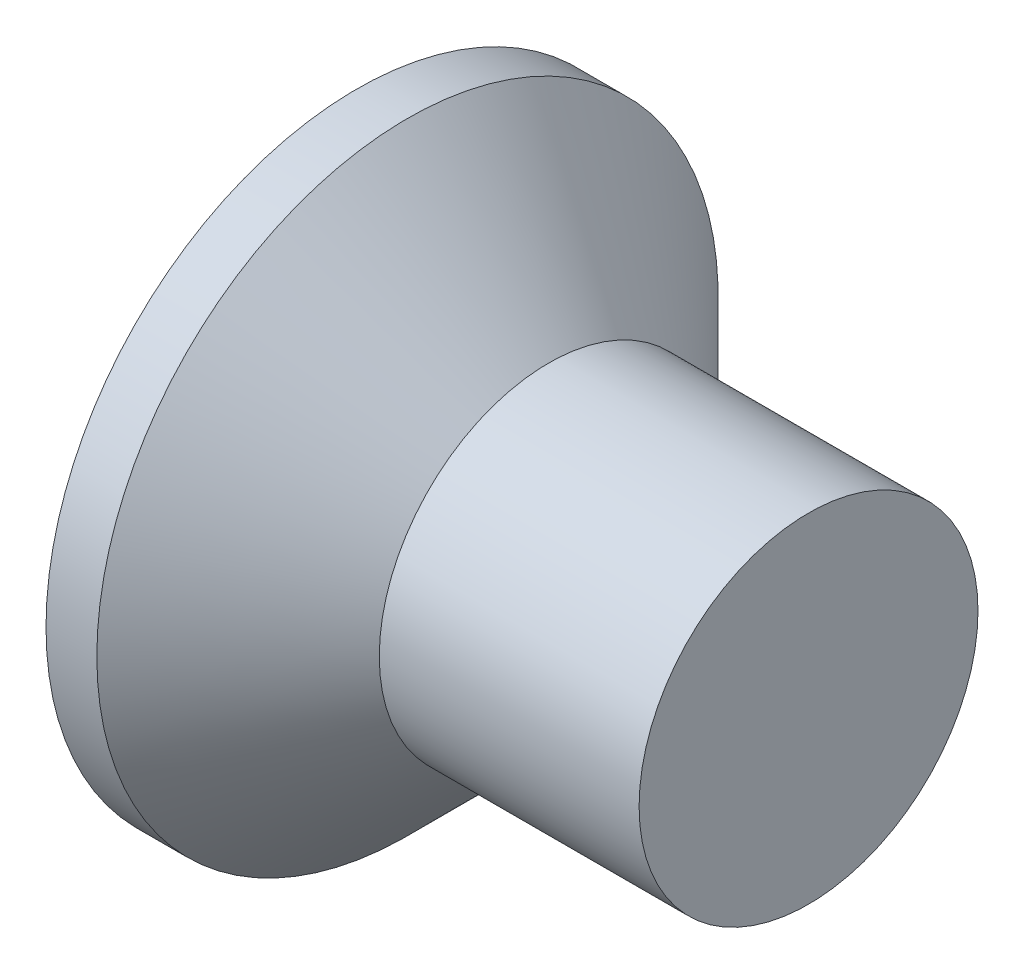
SolidWorks part; units mm, degrees
material "Plain Carbon Steel"
ref_plane "Plane1" through (0, 0, 0) normal (0, 0, 1) x (1, 0, 0)
ref_plane "Plane2" through (0, 0, 0) normal (0, 1, 0) x (1, 0, 0)
ref_plane "Plane3" through (0, 0, 0) normal (1, 0, 0) x (0, 0, -1)
sketch "BodySke" plane through (0, 0, 0) normal (0, 0, 1) x (1, 0, 0)
  line L0 (0, 0) -> (0, 2.75)
  line L1 (0, 2.75) -> (0.45, 2.75)
  line L2 (1.7, 1.5) -> (4, 1.5)
  line L3 (4, 1.5) -> (4, 0)
  line L4 (4, 0) -> (0, 0)
  line L5 (-6.35, 0) -> (82.55, 0) construction
  line L6 (1.7, -1.5) -> (4, -1.5) construction
  line L7 (0.45, -2.75) -> (1.7, -1.5) construction
  line L8 (0.45, 2.75) -> (1.7, 1.5)
  line L9 (0, -2.75) -> (0.45, -2.75) construction
  line L10 (2.2, 3.0875) -> (2.2, -6.4375) construction
  line L11 (0, 6.35) -> (0, -3.175) construction
  dimension "Diameter" = 3
  dimension "Length" = 4
  dimension "Head_ht" = 1.7
  dimension "Head_dia" = 5.5
  dimension "Head_ang" = 90
  dimension "D6" = 0.45
  dimension "Advance" = 0.5
  dimension "Thread_nom" = 4
revolve "Base-Revolve" add sketch "BodySke" angle 360 about L5
cosmetic thread "ThreadCosmetic" [suppressed] parameters "Thread_length"=1.8, "Thread_minor"=2.439
sketch "Sketch2" plane through (0, 0, 0) normal (-1, 0, 0) x (0, 0, 1)
  line L0 (-2.75, -0.5) -> (2.75, -0.5)
  line L1 (-2.75, -0.5) -> (-2.75, 0.5)
  line L2 (2.75, 0.5) -> (-2.75, 0.5)
  line L3 (2.75, 0.5) -> (2.75, -0.5)
  dimension "D1" = 0.5
  dimension "Slot_width" = 1
  dimension "D2" = 5.5
  dimension "D3" = 2.75
extrude "Slot" [suppressed] cut sketch "Sketch2" against normal blind 0.9
sketch "Sketch3" plane through (0, 0, 0) normal (-1, 0, 0) x (0, 0, 1)
  line L0 (-0.395, 1.55) -> (0.395, 1.55)
  line L1 (0.395, 1.55) -> (0.395, -1.55)
  line L2 (0.395, -1.55) -> (-0.395, -1.55)
  line L3 (-0.395, -1.55) -> (-0.395, 1.55)
  dimension "D1" = 1.55
  dimension "Cross_dia" = 3.1
  dimension "D2" = 0.395
  dimension "Cross_width" = 0.79
ref_plane "Plane4" through (2.08, 0, 0) normal (-1, 0, 0) x (0, 0, 1)
sketch "Sketch4" plane through (2.08, 0, 0) normal (-1, 0, 0) x (0, 0, 1)
  line L0 (-0.1975, 0.1975) -> (0.1975, 0.1975)
  line L3 (0.1975, 0.1975) -> (0.1975, -0.1975)
  line L4 (0.1975, -0.1975) -> (-0.1975, -0.1975)
  line L5 (-0.1975, -0.1975) -> (-0.1975, 0.1975)
  dimension "D1" = 0.395
  dimension "D2" = 0.395
  dimension "D3" = 0.1975
  dimension "D4" = 0.1975
loft "Cross" cut profiles "Sketch3", "Sketch4"
pattern_circular "CirPattern1" count 2 every 90 about axis through (0, 0, 0) along (1, 0, 0) of "Cross"
sketch "ThdSchSke" plane through (0, 0, 0) normal (0, 0, 1) x (1, 0, 0)
  line L0 (2.2, -1.2195) -> (2.0036, -1.5)
  line L1 (2.2, -1.2195) -> (2.3964, -1.5)
  line L2 (2.3964, -1.5) -> (2.3964, -1.875)
  line L3 (-3.175, 0) -> (5.1513, 0) construction
  line L5 (2.3964, -1.875) -> (2.0036, -1.875)
  line L6 (2.0036, -1.875) -> (2.0036, -1.5)
  line L7 (0, 2.75) -> (0, -2.75) construction
  dimension "Thread_minor" = 2.439
  dimension "Diameter" = 3
  dimension "Start" = 2.2
  dimension "SideAngle" = 55
  dimension "VeeAngle" = 70
  dimension "Overcut" = 3.75
revolve "ThreadSchematic" [suppressed] cut sketch "ThdSchSke" angle 360 about L3
pattern_linear "ThdSchPat" [suppressed]
equation "\"D1@Sketch3\" = \"Cross_dia@Sketch3\" / 2"
equation "\"D2@Sketch3\" = \"Cross_width@Sketch3\" / 2"
equation "\"D1@Sketch4\" = \"Cross_width@Sketch3\" *.5"
equation "\"D2@Sketch4\" = \"D1@Sketch4\""
equation "\"D4@Sketch4\" = \"D2@Sketch4\" / 2"
equation "\"D3@Sketch4\" = \"D1@Sketch4\" / 2"
equation "\"D1@Sketch2\" = \"Slot_width@Sketch2\" / 2"
equation "\"D2@Sketch2\" = \"Head_dia@BodySke\""
equation "\"D3@Sketch2\" = \"D2@Sketch2\" / 2"
equation "\"Thread_length@ThreadCosmetic\" = ((sgn( (\"Length@BodySke\" - \"Advance@BodySke\" - \"Head_ht@BodySke\" ) - \"Thread_nom@BodySke\" )-1)*( (\"Length@BodySke\" - \"Advance@BodySke\" - \"Head_ht@BodySke\" ) - \"Thread_nom@BodySke\" ))/-2+ \"Thread_nom@BodySke\""
equation "\"Thread_minor@ThdSchSke\" = \"Thread_minor@ThreadCosmetic\""
equation "\"Diameter@ThdSchSke\" = \"Diameter@BodySke\""
equation "\"Overcut@ThdSchSke\" = \"Diameter@BodySke\" * 1.25"
equation "\"Start@ThdSchSke\" = 0.000001 + \"Length@BodySke\" - \"Thread_length@ThreadCosmetic\"  '---Countersunk---"
equation "\"Num_threads@ThdSchPat\" = int( \"Thread_length@ThreadCosmetic\" / \"Advance@BodySke\" + 0.999 )  + 1"
equation "\"Advance@ThdSchPat\" = \"Thread_length@ThreadCosmetic\" /  (\"Num_threads@ThdSchPat\" - 1) 'relax it"
